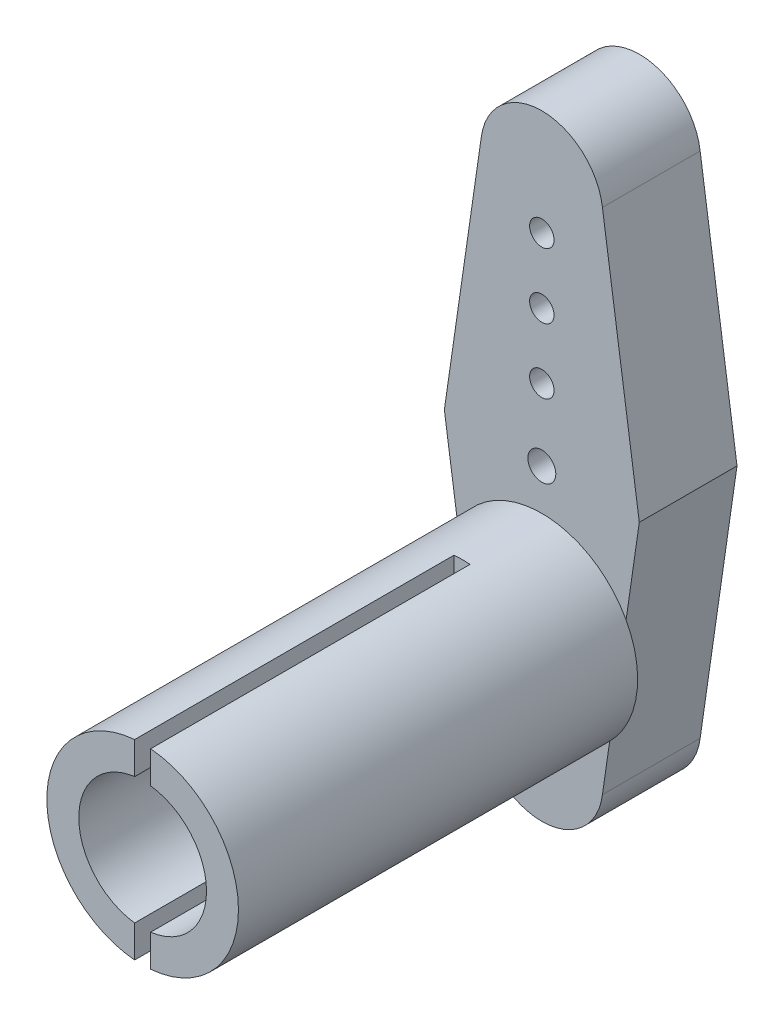
SolidWorks part; units mm, degrees
ref_plane "Front Plane" through (0, 0, 0) normal (0, 0, 1) x (1, 0, 0)
ref_plane "Top Plane" through (0, 0, 0) normal (0, 1, 0) x (1, 0, 0)
ref_plane "Right Plane" through (0, 0, 0) normal (1, 0, 0) x (0, 0, -1)
sketch "Sketch2" plane through (0, 0, 0) normal (0, 0, 1) x (1, 0, 0)
  line L0 (0, -55) -> (0, 55) construction
  line L1 (-6, 0) -> (-3.7206, -15.7189)
  line L2 (6, 0) -> (3.7206, -15.7189)
  arc A0 (6, 0) -> (-6, 0) centre (0, 0) ccw
  arc A1 (-3.7206, -15.7189) -> (3.7206, -15.7189) centre (0, -15.25) ccw
  dimension "D1" = 12
  dimension "D2" = 7.5
  dimension "D3" = 19
extrude "Boss-Extrude1" add sketch "Sketch2" along normal blind 6
sketch "Sketch3" plane through (0, 0, 0) normal (0, 0, 1) x (1, 0, 0)
  line L0 (-3.75, 0) -> (-2.25, -15)
  line L1 (2.25, -15) -> (3.75, 0)
  line L2 (0, -3.3) -> (0, 3.3) construction
  arc A0 (3.75, 0) -> (-3.75, 0) centre (0, 0) ccw
  arc A1 (-2.25, -15) -> (2.25, -15) centre (0, -15) ccw
  dimension "D1" = 7.5
  dimension "D2" = 4.5
  dimension "D3" = 15
extrude "Cut-Extrude3" cut sketch "Sketch3" along normal blind 4.7
sketch "Sketch4" plane through (0, 0, 4.7) normal (0, 0, -1) x (-1, 0, 0)
  circle A0 centre (0, 0) radius 0.75
  dimension "D1" = 1.5
extrude "Cut-Extrude4" cut sketch "Sketch4" against normal through all both and the other way through all
sketch "Sketch6" plane through (0, 0, 4.7) normal (0, 0, -1) x (-1, 0, 0)
  line L0 (0, 55) -> (0, -55) construction
  line L1 (55, 0) -> (-55, 0) construction
  circle A0 centre (0, -4.5) radius 0.75
  dimension "D1" = 1.5
  dimension "D2" = 4.5
extrude "Cut-Extrude6" cut sketch "Sketch6" against normal through all both and the other way through all
pattern_linear "LPattern1" count 3 spacing 4 along (0, -1, 0) of "Cut-Extrude6"
scale "Scale1" scale about centroid uniform scaling yes scale factor 1.02
sketch "Sketch7" plane through (0, 0, 0) normal (0, 1, 0) x (1, 0, 0)
  line L1 (-6.12, 0.0687) -> (6.12, 0.0687)
  line L2 (-6.12, 0.0687) -> (-6.12, -6.0513)
  line L3 (-6.12, -6.0513) -> (6.12, -6.0513)
  line L4 (6.12, 0.0687) -> (6.12, -6.0513)
extrude "Cut-Extrude7" cut sketch "Sketch7" along normal through all
mirror "Mirror3" about plane through (0, 0, 0) normal (0, 1, 0) of bodies 108
sketch "Sketch8" plane through (0, 0, 6.0513) normal (0, 0, 1) x (1, 0, 0)
  circle A0 centre (0, 0) radius 0.875
  dimension "D1" = 1.75
extrude "Cut-Extrude8" cut sketch "Sketch8" against normal through all
sketch "Sketch9" plane through (0, 0, 6.0513) normal (0, 0, 1) x (1, 0, 0)
  circle A3 centre (0, -8.562) radius 6
  circle A4 centre (0, -8.562) radius 4
  dimension "D1" = 12
  dimension "D2" = 8
extrude "Boss-Extrude2" add sketch "Sketch9" along normal blind 25
sketch "Sketch10" plane through (0, 0, 0) normal (0, 1, 0) x (1, 0, 0)
  line L0 (-6, -31.0513) -> (6, -31.0513) construction
  line L1 (-0.5, -51.0513) -> (0.5, -51.0513)
  line L2 (-0.5, -51.0513) -> (-0.5, -11.0513)
  line L3 (-0.5, -11.0513) -> (0.5, -11.0513)
  line L4 (0.5, -51.0513) -> (0.5, -11.0513)
  line L5 (-0.5, -51.0513) -> (0.5, -11.0513) construction
  line L6 (-0.5, -11.0513) -> (0.5, -51.0513) construction
  point P0 (0, -31.0513)
  dimension "D1" = 1
  dimension "D2" = 20
extrude "Cut-Extrude9" cut sketch "Sketch10" against normal through all
